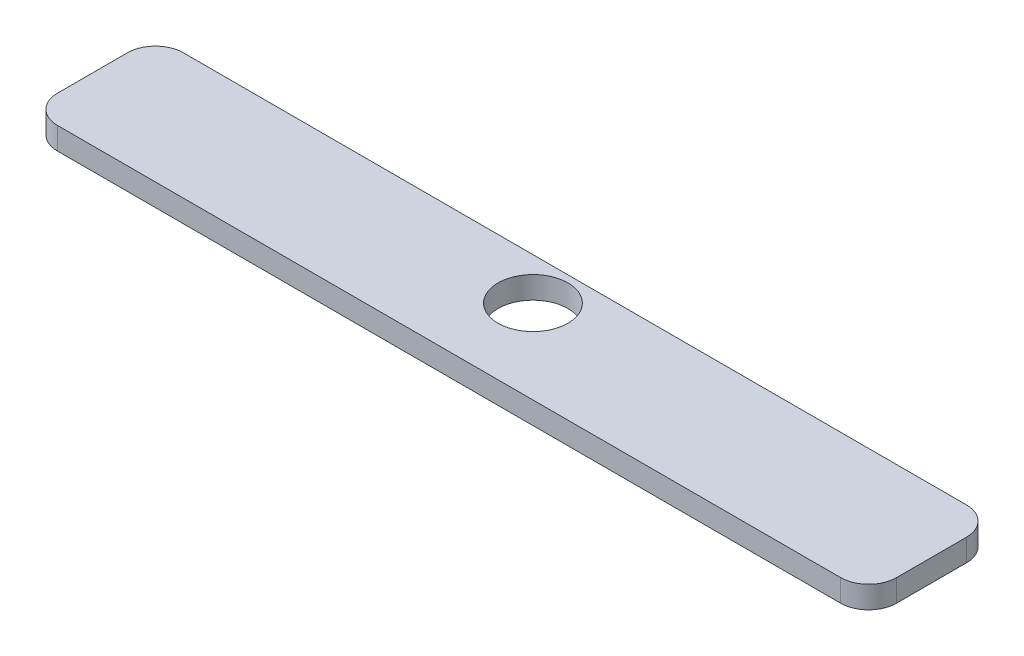
SolidWorks part; units mm, degrees
ref_plane "Front Plane" through (0, 0, 0) normal (0, 0, 1) x (1, 0, 0)
ref_plane "Top Plane" through (0, 0, 0) normal (0, 1, 0) x (1, 0, 0)
ref_plane "Right Plane" through (0, 0, 0) normal (1, 0, 0) x (0, 0, -1)
sketch "Sketch1" plane through (0, 0, 0) normal (0, 1, 0) x (1, 0, 0)
  line L1 (0, 0) -> (30, 0)
  line L2 (0, 0) -> (0, 4.5)
  line L3 (0, 4.5) -> (30, 4.5)
  line L4 (30, 0) -> (30, 4.5)
  circle A0 centre (15, 3) radius 1.25
  point P7 (0, 0)
  point P8 (15, 4.5)
  dimension "D4" = 2.5
  dimension "D1" = 4.5
  dimension "D2" = 30
  dimension "D3" = 1.5
extrude "Boss-Extrude1" add sketch "Sketch1" along normal blind 0.7937
fillet "Fillet1" radius 1 4 edges at (30, 0.3969, -4.5) (30, 0.3969, 0) (0, 0.3969, 0) (0, 0.3969, -4.5)
